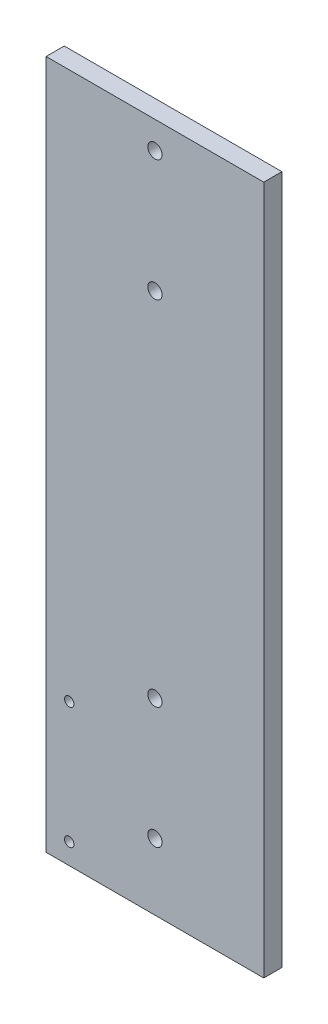
SolidWorks part; units mm, degrees
material "Low Carbon Steel"
ref_plane "Front Plane" through (0, 0, 0) normal (0, 0, 1) x (1, 0, 0)
ref_plane "Top Plane" through (0, 0, 0) normal (0, 1, 0) x (1, 0, 0)
ref_plane "Right Plane" through (0, 0, 0) normal (1, 0, 0) x (0, 0, -1)
sketch "Sketch1" plane through (0, 0, 0) normal (0, 0, 1) x (1, 0, 0)
  line L1 (38.1, 120.65) -> (-38.1, 120.65)
  line L2 (38.1, 120.65) -> (38.1, -120.65)
  line L3 (38.1, -120.65) -> (-38.1, -120.65)
  line L4 (-38.1, 120.65) -> (-38.1, -120.65)
  line L5 (38.1, 120.65) -> (-38.1, -120.65) construction
  line L6 (38.1, -120.65) -> (-38.1, 120.65) construction
  point P0 (0, 0)
  dimension "D1" = 241.3
  dimension "D2" = 76.2
extrude "Boss-Extrude1" add sketch "Sketch1" along normal blind 6.35
hole_wizard "M6 Tapped Hole1" positions "Sketch3" profile "Sketch2" tap size "M6" standard "Peddi DIN" end condition through all
sketch "Sketch3" plane through (0, 0, 6.35) normal (0, 0, 1) x (1, 0, 0)
  line L3 (0, 111.125) -> (0, 120.65) construction
  line L5 (0, 111.125) -> (0, -54.875) construction
  line L6 (0, -54.875) -> (0, -97.375) construction
  line L8 (38.1, 120.65) -> (-38.1, 120.65) construction
  point P0 (0, -97.375)
  point P2 (0, 111.125)
  point P19 (0, -54.875)
  point P32 (0, 68.625)
  dimension "D1" = 208.5
  dimension "D2" = 9.525
  dimension "D3" = 166
  dimension "D4" = 166
sketch "Sketch2" plane through (0, -97.375, 6.35) normal (1, 0, 0) x (0, -1, 0)
  line L0 (0, 0) -> (0, 6.35)
  line L1 (0, 6.35) -> (2.5, 6.35)
  line L2 (2.5, 6.35) -> (2.5, 0)
  line L5 (2.5, 0) -> (0, 0)
  line L11 (0, -6.35) -> (0, 107.95) construction
  dimension "Thru Tap Drill Dia." = 5
  dimension "Thru Tap Drill Depth" = 6.35
cosmetic thread "Hole Thread1" parameters "D2"=6
cosmetic thread "Hole Thread2" parameters "D2"=6
cosmetic thread "Hole Thread3" parameters "D2"=6
cosmetic thread "Hole Thread6" parameters "D2"=6
hole_wizard "M4 Tapped Hole1" positions "Sketch4" profile "Sketch5" tap size "M4" standard "Peddi DIN" end condition through all
sketch "Sketch4" plane through (0, 0, 6.35) normal (0, 0, 1) x (1, 0, 0)
  line L0 (0, -54.875) -> (-30, -54.875) construction
  line L1 (-30, -54.875) -> (-30, -70.875) construction
  line L3 (0, -97.375) -> (-30, -97.375) construction
  line L4 (-30, -97.375) -> (-30, -113.375) construction
  point P0 (-30, -70.875)
  point P2 (-30, -113.375)
  dimension "D1" = 30
  dimension "D2" = 16
sketch "Sketch5" plane through (-30, -70.875, 6.35) normal (1, 0, 0) x (0, -1, 0)
  line L0 (0, 0) -> (0, 6.35)
  line L1 (0, 6.35) -> (1.65, 6.35)
  line L2 (1.65, 6.35) -> (1.65, 0)
  line L5 (1.65, 0) -> (0, 0)
  line L11 (0, -6.35) -> (0, 107.95) construction
  dimension "Thru Tap Drill Dia." = 3.3
  dimension "Thru Tap Drill Depth" = 6.35
cosmetic thread "Hole Thread4" parameters "D2"=4
cosmetic thread "Hole Thread5" parameters "D2"=4
other "Freeze***"
